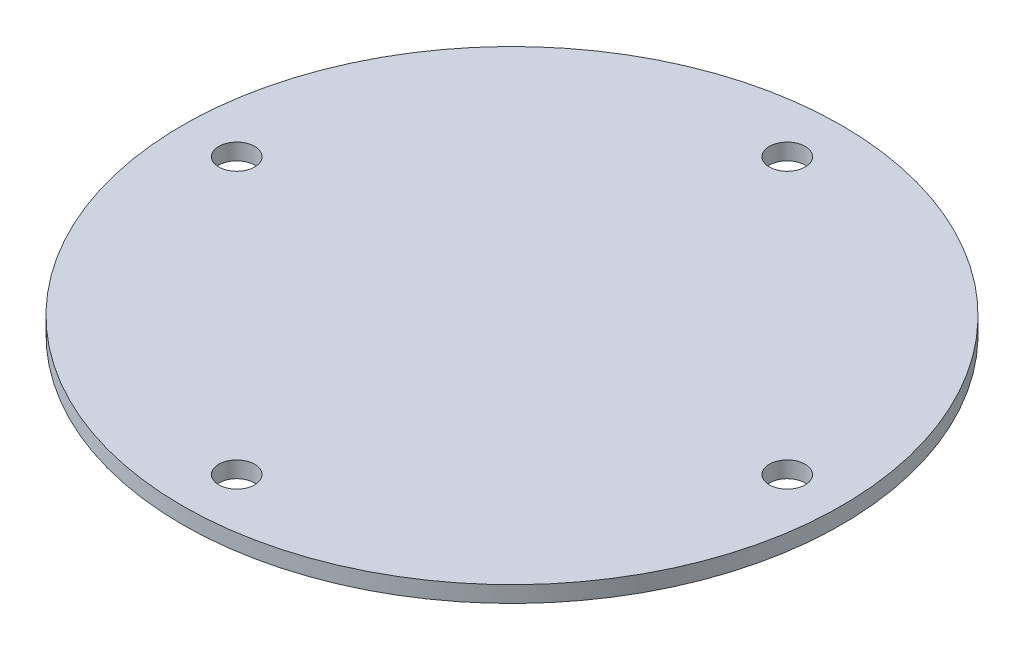
SolidWorks part; units mm, degrees
ref_plane "Front Plane" through (0, 0, 0) normal (0, 0, 1) x (1, 0, 0)
ref_plane "Top Plane" through (0, 0, 0) normal (0, 1, 0) x (1, 0, 0)
ref_plane "Right Plane" through (0, 0, 0) normal (1, 0, 0) x (0, 0, -1)
sketch "Sketch1" plane through (0, 0, 0) normal (0, 1, 0) x (1, 0, 0)
  circle A0 centre (0, 0) radius 60.7
  dimension "Diameter" = 121.4
extrude "Boss-Extrude1" add sketch "Sketch1" along normal mid plane 3
hole_wizard "M6 Clearance Hole1" positions "Sketch8" profile "Sketch9" hole size "M6" standard "ANSI Metric" end condition up to next
sketch "Sketch8" plane through (0, 1.5, 0) normal (0, 1, 0) x (1, 0, 0)
  line L0 (0, 0) -> (50.7, 0) construction
  point P0 (50.7, 0)
  dimension "ThreadedHoleDistance" = 50.7
sketch "Sketch9" plane through (50.7, 1.5, 0) normal (1, 0, 0) x (0, 0, 1)
  line L0 (0, 0) -> (0, 3)
  line L1 (0, 3) -> (3.3, 3)
  line L2 (3.3, 3) -> (3.3, 0)
  line L5 (3.3, 0) -> (0, 0)
  line L11 (0, -6.35) -> (0, 107.95) construction
  dimension "Thru Hole Dia." = 6.6
  dimension "Thru Hole Depth" = 3
pattern_circular "CirPattern2" count 4 over 360 about axis through (0, 0, 0) along (0, 1, 0) of "M6 Clearance Hole1"
sketch "Sketch5" [suppressed] plane through (0, 1.5, 0) normal (0, 1, 0) x (1, 0, 0)
  line L0 (0, 0) -> (65.4, 0) construction
  line L2 (0, 0) -> (39.1737, 39.1737) construction
  circle A0 centre (0, 0) radius 65.4 construction
  dimension "D1" = 45
  dimension " NoseShellHoleRadius" = 0
hole_wizard "M4 Clearance Hole1" [suppressed] positions "Sketch6" profile "Sketch7" hole size "M4" standard "ANSI Metric"
sketch "Sketch6" plane through (0, 1.5, 0) normal (0, 1, 0) x (1, 0, 0)
  point P0 (39.1737, 39.1737)
sketch "Sketch7" plane through (39.1737, 1.5, -39.1737) normal (1, 0, 0) x (0, 0, 1)
  line L0 (0, 0) -> (0, 3)
  line L1 (0, 3) -> (2.15, 3)
  line L2 (2.15, 3) -> (2.15, 0)
  line L5 (2.15, 0) -> (0, 0)
  line L11 (0, -6.35) -> (0, 107.95) construction
  dimension "Thru Hole Dia." = 4.3
  dimension "Thru Hole Depth" = 3
pattern_circular "CirPattern1" [suppressed] count 4 over 360
sketch "Sketch10" [suppressed] plane through (0, 1.5, 0) normal (0, 1, 0) x (1, 0, 0)
  circle A0 centre (0, 0) radius 7.5
  dimension "D1" = 15
extrude "Cut-Extrude1" [suppressed] cut sketch "Sketch10" against normal through all
sketch "Sketch11" [suppressed] plane through (0, -1.5, 0) normal (0, -1, 0) x (1, 0, 0)
  circle A0 centre (-14.75, -5) radius 2.25
  arc A1 (-16.7656, -6) -> (-16.7656, -4) centre (-14.75, -5) ccw construction
  circle A2 centre (-14.75, 5) radius 2.25
  circle A3 centre (34.75, -5) radius 2.25
  circle A4 centre (34.75, 5) radius 2.25
  arc A5 (-16.7656, 4) -> (-16.7656, 6) centre (-14.75, 5) ccw construction
  arc A6 (36.7656, 6) -> (36.7656, 4) centre (34.75, 5) ccw construction
  arc A7 (36.7656, -4) -> (36.7656, -6) centre (34.75, -5) ccw construction
extrude "Cut-Extrude2" [suppressed] cut sketch "Sketch11" against normal through all
sketch "Sketch12" [suppressed] plane through (0, 1.5, 0) normal (0, 1, 0) x (1, 0, 0)
  circle A0 centre (0, 0) radius 65.4 construction
  circle A1 centre (0, 0) radius 65.4
sketch "Sketch13" [suppressed] plane through (0, 1.5, 0) normal (0, 1, 0) x (1, 0, 0)
  line L0 (33.5571, -56.1345) -> (22.4418, -39.5077)
  line L1 (22.4418, -39.5077) -> (27.9287, -35.8397)
  line L2 (27.9287, -35.8397) -> (39.0439, -52.4665)
  line L3 (25.1853, -37.6737) -> (36.3468, -54.3698) construction
  line L4 (25.1853, -37.6737) -> (0, 0) construction
  line L5 (0, 0) -> (0, -55.4) construction
  line L6 (-7.3072, -48.0722) -> (-7.2822, -48.1318)
  line L7 (-7.3072, -48.0722) -> (-7.2822, -48.1318) construction
  line L8 (5.9654, -54.6476) -> (4.6633, -61.2016)
  line L9 (5.9654, -54.6476) -> (4.6633, -61.2016) construction
  line L10 (-13.8383, -61.9557) -> (-10.6131, -45.7223)
  line L11 (-13.8383, -61.9557) -> (-10.6131, -45.7223) construction
  line L12 (-10.6131, -45.7223) -> (-9.717, -41.2115)
  line L13 (-10.6131, -45.7223) -> (-9.717, -41.2115) construction
  line L14 (-9.717, -41.2115) -> (-8.0847, -32.9958)
  line L15 (-9.717, -41.2115) -> (-8.0847, -32.9958) construction
  line L16 (-8.0847, -32.9958) -> (-7.2796, -28.9433)
  line L17 (-8.0847, -32.9958) -> (-7.2796, -28.9433) construction
  line L18 (-7.2796, -28.9433) -> (-2.2975, -3.8666)
  line L19 (-7.2796, -28.9433) -> (-2.2975, -3.8666) construction
  line L20 (-2.2975, -3.8666) -> (0.645, -4.4512)
  line L21 (-2.2975, -3.8666) -> (0.645, -4.4512) construction
  line L22 (0.645, -4.4512) -> (-4.3371, -29.5279)
  line L23 (0.645, -4.4512) -> (-4.3371, -29.5279) construction
  line L24 (-4.3371, -29.5279) -> (-5.1422, -33.5804)
  line L25 (-4.3371, -29.5279) -> (-5.1422, -33.5804) construction
  line L26 (-5.1422, -33.5804) -> (-6.7745, -41.7961)
  line L27 (-5.1422, -33.5804) -> (-6.7745, -41.7961) construction
  line L28 (-6.7745, -41.7961) -> (-7.6706, -46.3069)
  line L29 (-6.7745, -41.7961) -> (-7.6706, -46.3069) construction
  circle A0 centre (0, 0) radius 65.4 construction
  circle A1 centre (0, 0) radius 65.4
  arc A2 (33.5571, -56.1345) -> (39.0439, -52.4665) centre (0, 0) ccw
  arc A3 (-7.2822, -48.1318) -> (0.9663, -48.6742) centre (0.0376, 0.1893) ccw
  arc A4 (-7.2822, -48.1318) -> (0.9663, -48.6742) centre (0.0376, 0.1893) ccw construction
  arc A5 (5.9654, -54.6476) -> (0.9663, -48.6742) centre (1.0613, -53.6733) ccw
  arc A6 (5.9654, -54.6476) -> (0.9663, -48.6742) centre (1.0613, -53.6733) ccw construction
  arc A7 (-0.2638, -65.2272) -> (4.6633, -61.2016) centre (-0.2408, -60.2272) ccw
  arc A8 (-0.2638, -65.2272) -> (4.6633, -61.2016) centre (-0.2408, -60.2272) ccw construction
  arc A9 (-10.5087, -64.3722) -> (-0.2638, -65.2272) centre (0.0376, 0.1893) ccw
  arc A10 (-10.5087, -64.3722) -> (-0.2638, -65.2272) centre (0.0376, 0.1893) ccw construction
  spline S0 degree 3 poles (-851.9646, -2942.8185) (60.4248, -65.7152) (17.8504, -79.9431) (-12.3758, -63.3729) (-13.1243, -62.9075) (-13.5648, -62.5349) (-13.7339, -62.3268) (-13.8027, -62.2127) (-15.1865, -57.8662) (54.9429, -40.9019) (-2900.9164, -875.9568) knots -23.643273 -23.643273 -23.643273 -23.643273 0.25 0.5 0.75 0.875 0.90625 0.9375 0.96875 4.171829 4.171829 4.171829 4.171829 only from (-10.5087, -64.3722) to (-13.8383, -61.9557)
  spline S1 degree 3 poles (-10.5087, -64.3722) (-10.8215, -64.2088) (-11.4465, -63.8823) (-12.3758, -63.3729) (-13.1243, -62.9075) (-13.5648, -62.5349) (-13.7339, -62.3268) (-13.8027, -62.2127) (-13.8424, -62.0879) (-13.8422, -62) (-13.8383, -61.9557) knots 0 0 0 0 0.25 0.5 0.75 0.875 0.90625 0.9375 0.96875 1 1 1 1 construction
  spline S2 degree 3 poles (-3007.5234, -22.9557) (34.2167, -32.9245) (-7.4634, -39.6228) (-7.7013, -46.6474) (-7.6977, -46.7608) (-7.6875, -46.8738) (-7.6712, -46.9863) (-7.6495, -47.098) (-7.5964, -47.3201) (-3.3838, -59.7446) (38.0106, -60.1077) (-2841.7572, -1030.2239) knots -11.347292 -11.347292 -11.347292 -11.347292 0.125 0.1875 0.25 0.3125 0.375 0.4375 0.5 0.75 21.8368 21.8368 21.8368 21.8368 only from (-7.6706, -46.3069) to (-7.3072, -48.0722)
  spline S3 degree 3 poles (-7.6706, -46.3069) (-7.6813, -46.3825) (-7.6961, -46.496) (-7.7013, -46.6474) (-7.6977, -46.7608) (-7.6875, -46.8738) (-7.6712, -46.9863) (-7.6495, -47.098) (-7.5964, -47.3201) (-7.4857, -47.6466) (-7.3668, -47.9303) (-7.3072, -48.0722) knots 0 0 0 0 0.125 0.1875 0.25 0.3125 0.375 0.4375 0.5 0.75 1 1 1 1 construction
  dimension "D2" = 7
  dimension "D3" = 20
  dimension "D4" = 46
  dimension "D1" = 0
extrude "Cut-Extrude3" [suppressed] cut sketch "Sketch13" against normal through all
pattern_circular "CirPattern3" [suppressed] count 4 over 360
